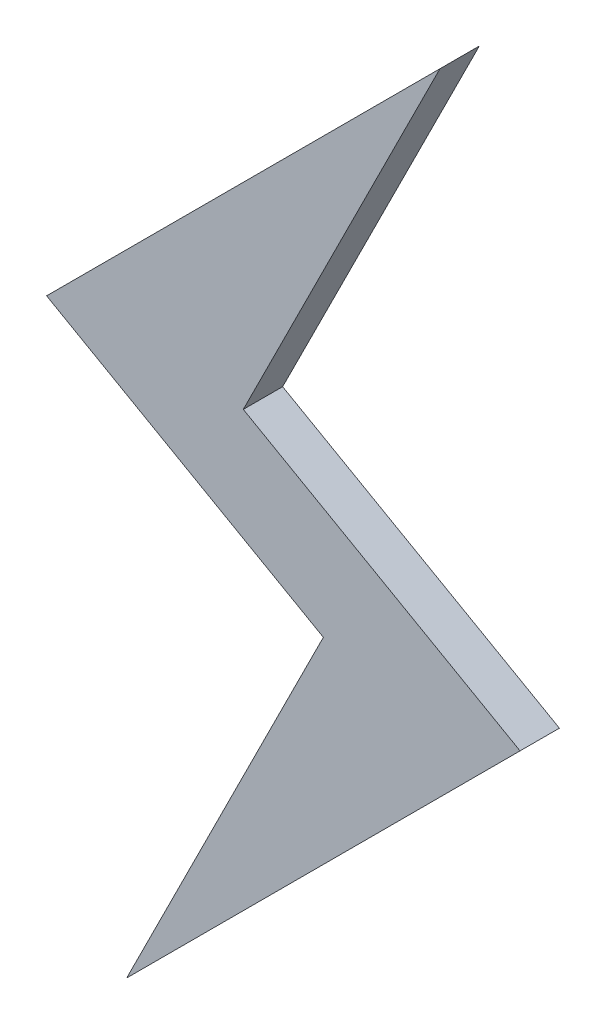
SolidWorks part; units mm, degrees
ref_plane "Front" through (0, 0, 0) normal (0, 0, 1) x (1, 0, 0)
ref_plane "Top" through (0, 0, 0) normal (0, 1, 0) x (1, 0, 0)
ref_plane "Right" through (0, 0, 0) normal (1, 0, 0) x (0, 0, -1)
sketch "草图1" plane through (0, 0, 0) normal (0, 0, 1) x (1, 0, 0)
  line L0 (0, 0) -> (50, 50)
  line L1 (50, 50) -> (25, 0)
  line L2 (25, 0) -> (60.1772, -20)
  line L3 (60.1772, -20) -> (10.1772, -70)
  line L4 (10.1772, -70) -> (35.1772, -20)
  line L5 (35.1772, -20) -> (0, 0)
  dimension "D1" = 50
  dimension "D2" = 50
  dimension "D3" = 25
  dimension "D4" = 50
  dimension "D5" = 25
  dimension "D6" = 20
extrude "凸台-拉伸1" add sketch "草图1" along normal blind 5
